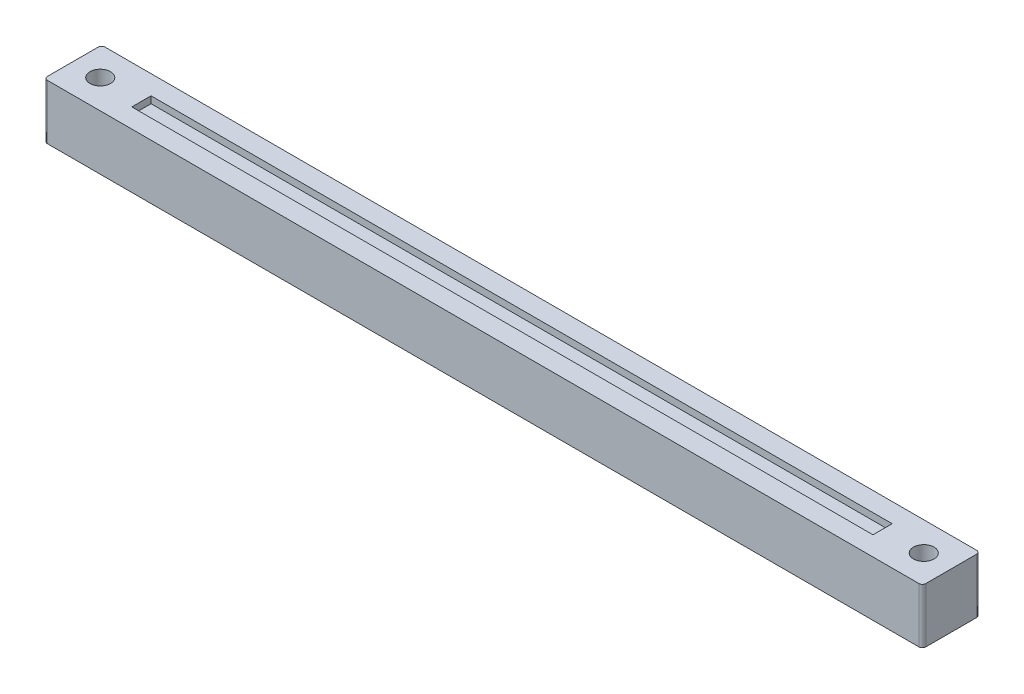
SolidWorks part; units mm, degrees
ref_plane "Front Plane" through (0, 0, 0) normal (0, 0, 1) x (1, 0, 0)
ref_plane "Top Plane" through (0, 0, 0) normal (0, 1, 0) x (1, 0, 0)
ref_plane "Right Plane" through (0, 0, 0) normal (1, 0, 0) x (0, 0, -1)
sketch "Sketch1" plane through (0, 0, 0) normal (0, 1, 0) x (1, 0, 0)
  line L1 (-64, -4.2) -> (64, -4.2)
  line L2 (-64, -4.2) -> (-64, 4.2)
  line L3 (-64, 4.2) -> (64, 4.2)
  line L4 (64, -4.2) -> (64, 4.2)
  line L5 (-64, -4.2) -> (64, 4.2) construction
  line L6 (-64, 4.2) -> (64, -4.2) construction
  point P0 (0, 0)
  dimension "D1" = 128
  dimension "D2" = 8.4
extrude "Boss-Extrude1" add sketch "Sketch1" along normal blind 8
sketch "Sketch2" plane through (0, 8, 0) normal (0, 1, 0) x (1, 0, 0)
  line L0 (0, -4.2) -> (0, 4.2) construction
  line L1 (-64, -4.2) -> (64, -4.2) construction
  line L2 (64, 4.2) -> (-64, 4.2) construction
  line L3 (-64, 0) -> (64, 0) construction
  line L4 (-64, 4.2) -> (-64, -4.2) construction
  line L5 (64, -4.2) -> (64, 4.2) construction
  circle A0 centre (-60, 0) radius 1.5
  circle A1 centre (60, 0) radius 1.5
  dimension "D1" = 3
  dimension "D2" = 120
extrude "Cut-Extrude1" cut sketch "Sketch2" against normal through all
sketch "Sketch3" plane through (0, 8, 0) normal (0, 1, 0) x (1, 0, 0)
  line L1 (-54, -1.4) -> (54, -1.4)
  line L2 (-54, -1.4) -> (-54, 1.4)
  line L3 (-54, 1.4) -> (54, 1.4)
  line L4 (54, -1.4) -> (54, 1.4)
  line L5 (-54, -1.4) -> (54, 1.4) construction
  line L6 (-54, 1.4) -> (54, -1.4) construction
  point P0 (0, 0)
  dimension "D1" = 108
  dimension "D2" = 2.8
extrude "Cut-Extrude2" cut sketch "Sketch3" against normal blind 1
fillet "Fillet1" radius 0.5 4 edges at (64, 4, 4.2) (64, 4, -4.2) (-64, 4, -4.2) (-64, 4, 4.2)
